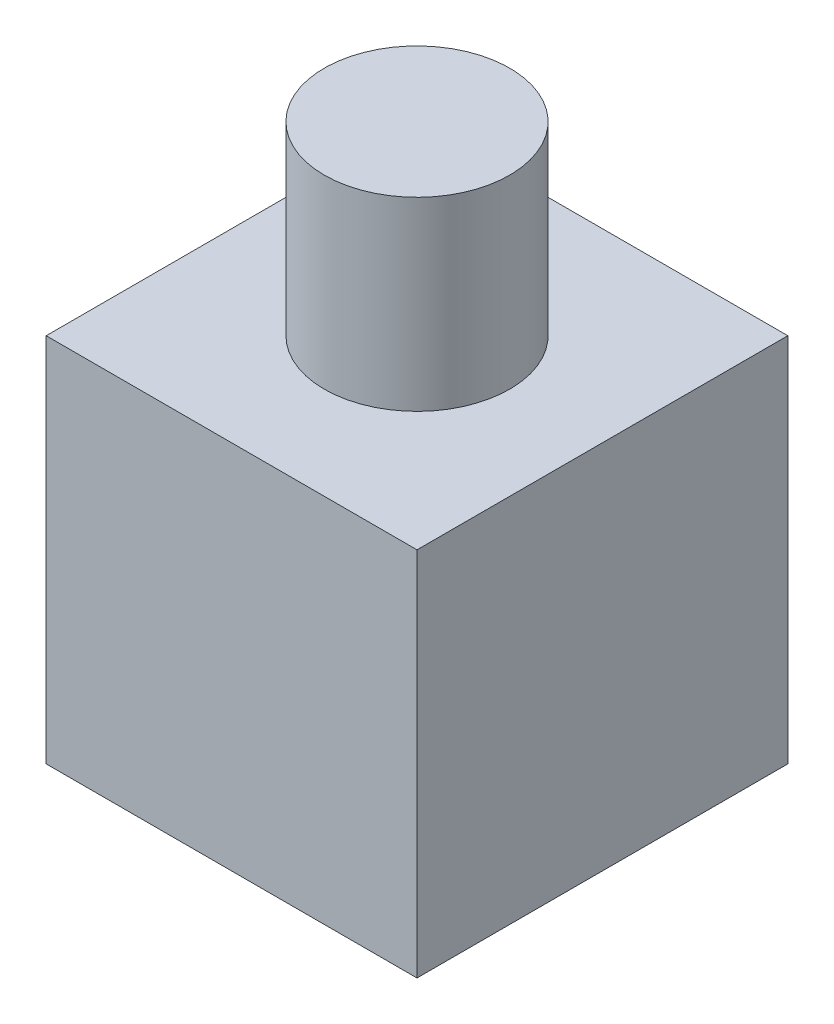
SolidWorks part; units mm, degrees
ref_plane "Front Plane" through (0, 0, 0) normal (0, 0, 1) x (1, 0, 0)
ref_plane "Top Plane" through (0, 0, 0) normal (0, 1, 0) x (1, 0, 0)
ref_plane "Right Plane" through (0, 0, 0) normal (1, 0, 0) x (0, 0, -1)
sketch "Sketch1" plane through (0, 0, 0) normal (0, 1, 0) x (1, 0, 0)
  line L1 (0, 0) -> (254, 0)
  line L2 (0, 0) -> (0, 254)
  line L3 (0, 254) -> (254, 254)
  line L4 (254, 0) -> (254, 254)
  dimension "D1" = 254
extrude "Boss-Extrude1" add sketch "Sketch1" along normal blind 254
sketch "Sketch2" plane through (0, 254, 0) normal (0, 1, 0) x (1, 0, 0)
  circle A0 centre (127, 127) radius 63.5
  dimension "D1" = 127
extrude "Boss-Extrude2" add sketch "Sketch2" along normal blind 127
